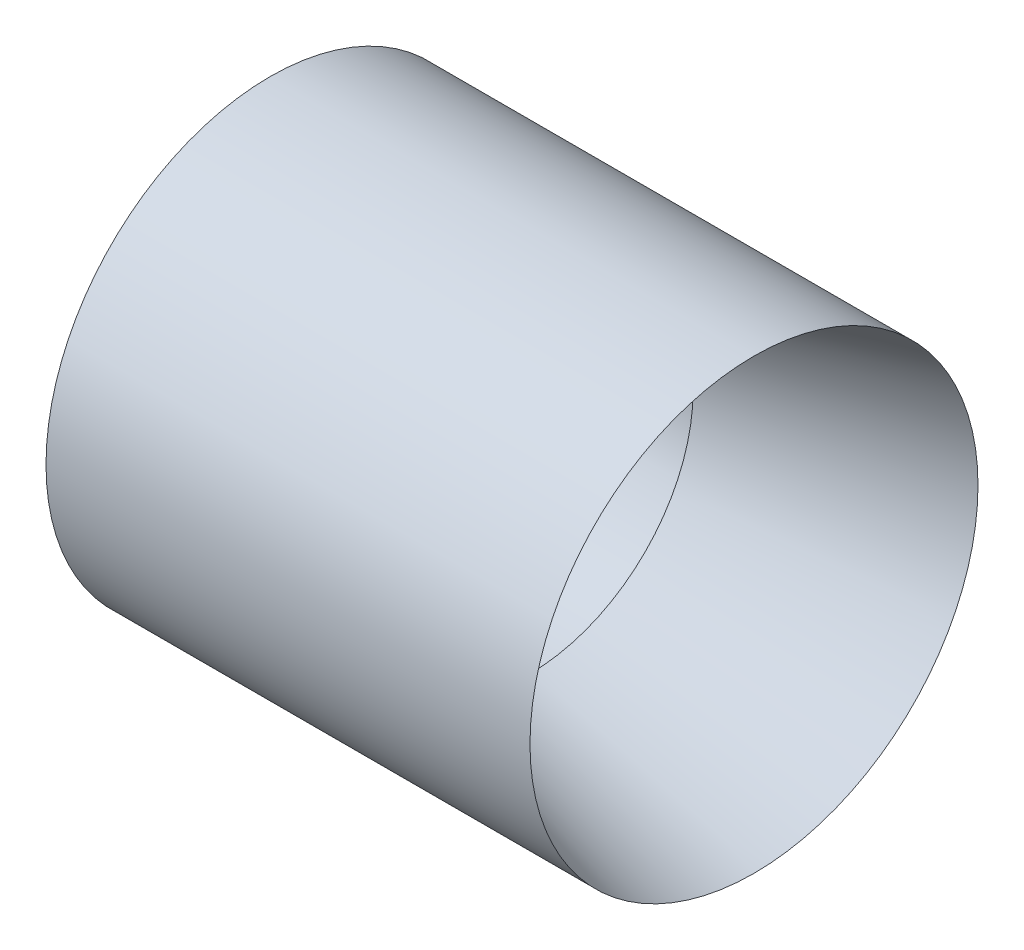
SolidWorks part; units mm, degrees
material "C (Graphite)"
ref_plane "Front Plane"
ref_plane "Top Plane" through (0, 0, 0) normal (0, 1, 0) x (1, 0, 0)
ref_plane "Right Plane" through (0, 0, 0) normal (1, 0, 0) x (0, 0, -1)
sketch "Sketch1" plane through (0, 0, 0) normal (0, 0, 1) x (1, 0, 0)
  line L0 (0, 57.319) -> (85.97, 57.319) construction
  line L1 (142.7452, 19.05) -> (162.4462, 19.05) construction
  line L2 (162.5027, 23.8732) -> (-363.7553, 392.363) construction
  line L3 (202.4525, 22.2956) -> (290.9373, 46.005) construction
  line L4 (324.51, 43.655) -> (465.1357, 51.0249) construction
  line L5 (0, 0) -> (174.3765, 0) construction
  line L6 (160.6575, 26.05) -> (216.9371, 26.05)
  line L7 (160.6575, 26.05) -> (170.6545, 19.05)
  line L8 (170.6545, 19.05) -> (190.8128, 19.05)
  line L9 (190.8128, 19.05) -> (216.9371, 26.05)
  arc A0 (85.97, 57.319) -> (162.5027, 23.8732) centre (91.4096, -34.52) cw construction
  arc A1 (162.5027, 23.8732) -> (177.8, 19.05) centre (177.8, 45.72) ccw construction
  arc A2 (177.8, 19.05) -> (202.4525, 22.2956) centre (177.8, 114.3) ccw construction
  parabola Q0 (202.4525, 22.2956) -> (324.51, 43.655) focus (420.2156, -29.3912) apex (456.9181, 5.2587) construction
  dimension "D5" = 92
  dimension "D6" = 26.67
  dimension "D7" = 95.25
  dimension "D1" = 35
  dimension "D2" = 57.319
  dimension "D3" = 85.97
  dimension "D4" = 177.8
  dimension "D8" = 19.05
  dimension "D10" = 3
  dimension "D11" = 43.655
  dimension "D12" = 146.71
  dimension "D9" = 15
  dimension "D13" = 7
revolve "Revolve1" add sketch "Sketch1" angle 360 about L5
equation "\"b\"= 35deg"
equation "\"D1@Sketch1\"=\"b\""
equation "\"Rc\"= 114.638 / 2mm"
equation "\"D2@Sketch1\"=\"Rc\""
equation "\"Lcyl\"= 85.97mm"
equation "\"D3@Sketch1\"=\"Lcyl\""
equation "\"Lc\"= 177.8mm"
equation "\"D4@Sketch1\"=\"Lc\""
equation "\"R2\"= 92mm"
equation "\"D5@Sketch1\"=\"R2\""
equation "\"R1\"= 26.67mm"
equation "\"D6@Sketch1\"=\"R1\""
equation "\"Rn\"= 95.25mm"
equation "\"D7@Sketch1\"=\"Rn\""
equation "\"Rt\"= 38.1mm / 2"
equation "\"D8@Sketch1\"=\"Rt\""
equation "\"Tn\"= 15deg"
equation "\"Te\"= 3deg"
equation "\"D10@Sketch1\"=\"Te\""
equation "\"Re\"= 87.31mm / 2"
equation "\"D11@Sketch1\"=\"Re\""
equation "\"Le\"= 146.71mm"
equation "\"D12@Sketch1\"=\"Le\""
equation "\"D9@Sketch1\"=\"Tn\""
